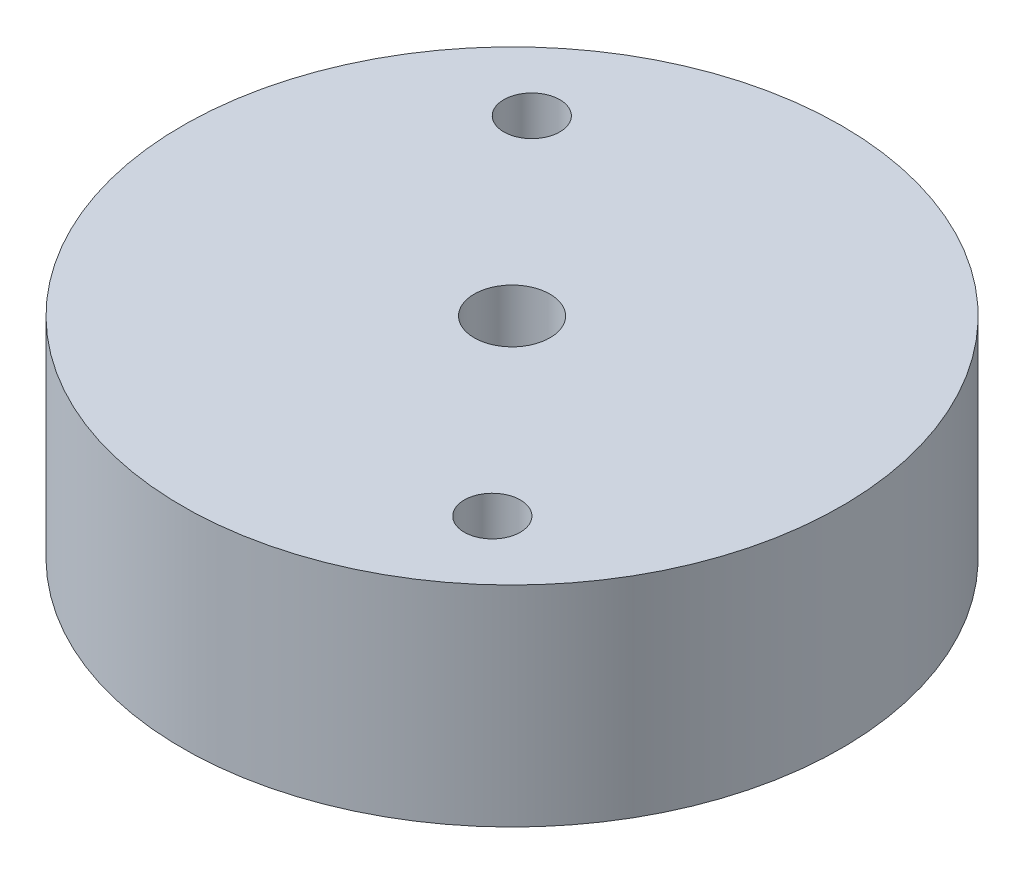
SolidWorks part; units mm, degrees
ref_plane "Front Plane" through (0, 0, 0) normal (0, 0, 1) x (1, 0, 0)
ref_plane "Top Plane" through (0, 0, 0) normal (0, 1, 0) x (1, 0, 0)
ref_plane "Right Plane" through (0, 0, 0) normal (1, 0, 0) x (0, 0, -1)
sketch "Sketch1" plane through (0, 0, 0) normal (0, 1, 0) x (1, 0, 0)
  circle A0 centre (0, 0) radius 10
  dimension "D1" = 20
extrude "Boss-Extrude1" add sketch "Sketch1" along normal blind 6.36
sketch "Sketch2" plane through (0, 6.36, 0) normal (0, 1, 0) x (1, 0, 0)
  circle A0 centre (0, 0) radius 1.15
  dimension "D1" = 2.3
extrude "Cut-Extrude1" cut sketch "Sketch2" against normal up to surface (6.36 mm away) up to face at (0, 0, 10)
sketch "Sketch3" plane through (0, 6.36, 0) normal (0, 1, 0) x (1, 0, 0)
  circle A1 centre (4.9598, -5.559) radius 0.85
  circle A2 centre (4.9598, -5.559) radius 0.85
  dimension "D1" = 0
extrude "Cut-Extrude2" cut sketch "Sketch3" against normal up to next
sketch "Sketch4" plane through (0, 6.36, 0) normal (0, 1, 0) x (1, 0, 0)
  circle A0 centre (-4.9598, 5.559) radius 0.85 construction
  circle A1 centre (-4.9598, 5.559) radius 0.85
extrude "Cut-Extrude3" cut sketch "Sketch4" against normal up to next
sketch "Sketch5" [suppressed] plane through (0, 0, 0) normal (0, -1, 0) x (1, 0, 0)
  circle A0 centre (6.8339, 2.9666) radius 0.85 construction
  circle A1 centre (-6.8339, -2.9666) radius 0.85 construction
  circle A2 centre (6.8339, 2.9666) radius 0.85
  circle A3 centre (-6.8339, -2.9666) radius 0.85
extrude "Cut-Extrude4" [suppressed] cut sketch "Sketch5" against normal up to next
